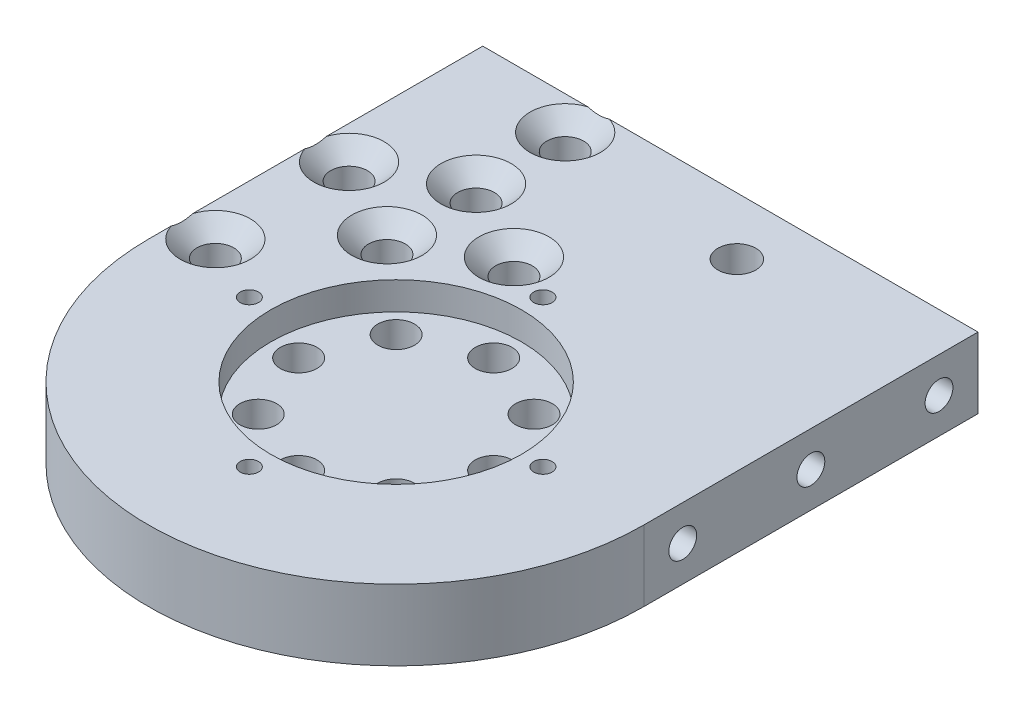
SolidWorks part; units mm, degrees
material "1060 合金"
ref_plane "前视基准面" through (0, 0, 0) normal (0, 0, 1) x (1, 0, 0)
ref_plane "上视基准面" through (0, 0, 0) normal (0, 1, 0) x (1, 0, 0)
ref_plane "右视基准面" through (0, 0, 0) normal (1, 0, 0) x (0, 0, -1)
sketch "草图1" plane through (0, 0, 0) normal (0, 1, 0) x (1, 0, 0)
  line L0 (0, 0) -> (88.9, 0)
  line L1 (88.9, 0) -> (88.9, -60)
  line L2 (0, 0) -> (0, -60)
  arc A0 (0, -60) -> (88.9, -60) centre (44.45, -60) ccw
  dimension "D2" = 88.9
  dimension "D1" = 88.9
  dimension "D3" = 60
extrude "凸台-拉伸1" add sketch "草图1" along normal blind 12.7
sketch "草图2" plane through (0, 12.7, 0) normal (0, 1, 0) x (1, 0, 0)
  circle A0 centre (44.45, -60) radius 22.5
  arc A1 (0, -60) -> (88.9, -60) centre (44.45, -60) ccw construction
  dimension "D2" = 45
extrude "切除-拉伸1" cut sketch "草图2" against normal blind 5
sketch "草图3" plane through (0, 7.7, 0) normal (0, 1, 0) x (1, 0, 0)
  circle A0 centre (44.45, -42.5) radius 3.3
  circle A1 centre (56.8244, -47.6256) radius 3.3
  circle A4 centre (61.95, -60) radius 3.3
  circle A5 centre (56.8244, -72.3744) radius 3.3
  circle A6 centre (44.45, -77.5) radius 3.3
  circle A7 centre (32.0756, -72.3744) radius 3.3
  circle A8 centre (26.95, -60) radius 3.3
  circle A9 centre (32.0756, -47.6256) radius 3.3
  dimension "D2" = 6.6
  dimension "D4" = 8
extrude "切除-拉伸2" cut sketch "草图3" against normal through all
sketch "草图4" plane through (0, 12.7, 0) normal (0, 1, 0) x (1, 0, 0)
  circle A0 centre (44.45, -33.65) radius 1.65
  circle A1 centre (70.8, -60) radius 1.65
  circle A4 centre (44.45, -86.35) radius 1.65
  circle A5 centre (18.1, -60) radius 1.65
  dimension "D3" = 3.3
  dimension "D4" = 4
extrude "切除-拉伸3" cut sketch "草图4" against normal through all
sketch "草图5" plane through (0, 12.7, 0) normal (0, 1, 0) x (1, 0, 0)
  line L0 (88.9, 0) -> (0, 0) construction
  line L1 (20.8, 6.637) -> (20.8, -54.7342) construction
  line L2 (0, 0) -> (0, -60) construction
  circle A0 centre (20.8, -6) radius 3.3
  circle A1 centre (20.8, -22) radius 3.3
  circle A2 centre (20.8, -38) radius 3.3
  dimension "D1" = 6.6
  dimension "D2" = 6.6
  dimension "D3" = 6.6
  dimension "D4" = 6
  dimension "D5" = 16
  dimension "D6" = 16
  dimension "D7" = 20.8
extrude "切除-拉伸4" cut sketch "草图5" against normal through all
sketch "草图6" plane through (0, 12.7, 0) normal (0, 1, 0) x (1, 0, 0)
  circle A0 centre (20.8, -6) radius 6.3
  circle A1 centre (20.8, -22) radius 6.3
  circle A2 centre (20.8, -38) radius 6.3
  dimension "D1" = 12.6
  dimension "D2" = 12.6
  dimension "D3" = 12.6
extrude "切除-拉伸5" cut sketch "草图6" against normal blind 3 draft 45
sketch "草图7" plane through (0, 12.7, 0) normal (0, 1, 0) x (1, 0, 0)
  line L0 (18.8791, 0) -> (0, 0) construction
  line L1 (0, 0) -> (0, -60) construction
  circle A0 centre (6, -30) radius 3.3
  circle A1 centre (6, -54) radius 3.3
  dimension "D1" = 6.6
  dimension "D2" = 6.6
  dimension "D3" = 30
  dimension "D4" = 6
  dimension "D5" = 24
  dimension "D6" = 6
extrude "切除-拉伸6" cut sketch "草图7" against normal through all
sketch "草图8" plane through (0, 12.7, 0) normal (0, 1, 0) x (1, 0, 0)
  circle A0 centre (6, -30) radius 6.3
  circle A1 centre (6, -54) radius 6.3
  dimension "D1" = 12.6
  dimension "D2" = 12.6
extrude "切除-拉伸7" cut sketch "草图8" against normal blind 3 draft 45
sketch "草图9" plane through (0, 12.7, 0) normal (0, 1, 0) x (1, 0, 0)
  line L0 (88.9, 0) -> (22.7209, 0) construction
  line L1 (0, 0) -> (0, -28.0791) construction
  circle A0 centre (35.6, -30) radius 3.3
  dimension "D1" = 6.6
  dimension "D2" = 30
  dimension "D3" = 35.6
extrude "切除-拉伸8" cut sketch "草图9" against normal through all
sketch "草图10" plane through (0, 12.7, 0) normal (0, 1, 0) x (1, 0, 0)
  circle A0 centre (35.6, -30) radius 6.3
  dimension "D1" = 12.6
extrude "切除-拉伸9" cut sketch "草图10" against normal blind 3 draft 45
sketch "草图11" plane through (0, 12.7, 0) normal (0, 1, 0) x (1, 0, 0)
  line L0 (88.9, 0) -> (22.7209, 0) construction
  line L1 (88.9, -60) -> (88.9, 0) construction
  circle A0 centre (55.92, -10.31) radius 3.4
  dimension "D2" = 6.8
  dimension "D1" = 10.31
  dimension "D3" = 32.98
extrude "切除-拉伸10" cut sketch "草图11" against normal through all
sketch "草图12" plane through (88.9, 0, 0) normal (1, 0, 0) x (0, 0, -1)
  line L0 (-60, 12.7) -> (0, 12.7) construction
  line L1 (0, 12.7) -> (0, 0) construction
  circle A0 centre (-7, 6.35) radius 2.5
  circle A1 centre (-30, 6.35) radius 2.5
  circle A2 centre (-53, 6.35) radius 2.5
  dimension "D1" = 5
  dimension "D4" = 5
  dimension "D5" = 5
  dimension "D2" = 6.35
  dimension "D3" = 7
  dimension "D6" = 23
  dimension "D7" = 23
  dimension "D8" = 6.35
  dimension "D9" = 6.35
extrude "切除-拉伸11" cut sketch "草图12" against normal blind 10
sketch "草图13" plane through (0, 0, 0) normal (0, 0, -1) x (-1, 0, 0)
  line L0 (0, 12.7) -> (0, 0) construction
  line L1 (-18.8791, 12.7) -> (0, 12.7) construction
  line L2 (-88.9, 12.7) -> (-22.7209, 12.7) construction
  circle A0 centre (-6, 6.35) radius 2.5
  circle A1 centre (-35.6, 6.35) radius 2.5
  dimension "D1" = 5
  dimension "D2" = 5
  dimension "D6" = 29.6
  dimension "D3" = 6
  dimension "D4" = 6.35
  dimension "D5" = 6.35
extrude "切除-拉伸12" cut sketch "草图13" against normal blind 15
